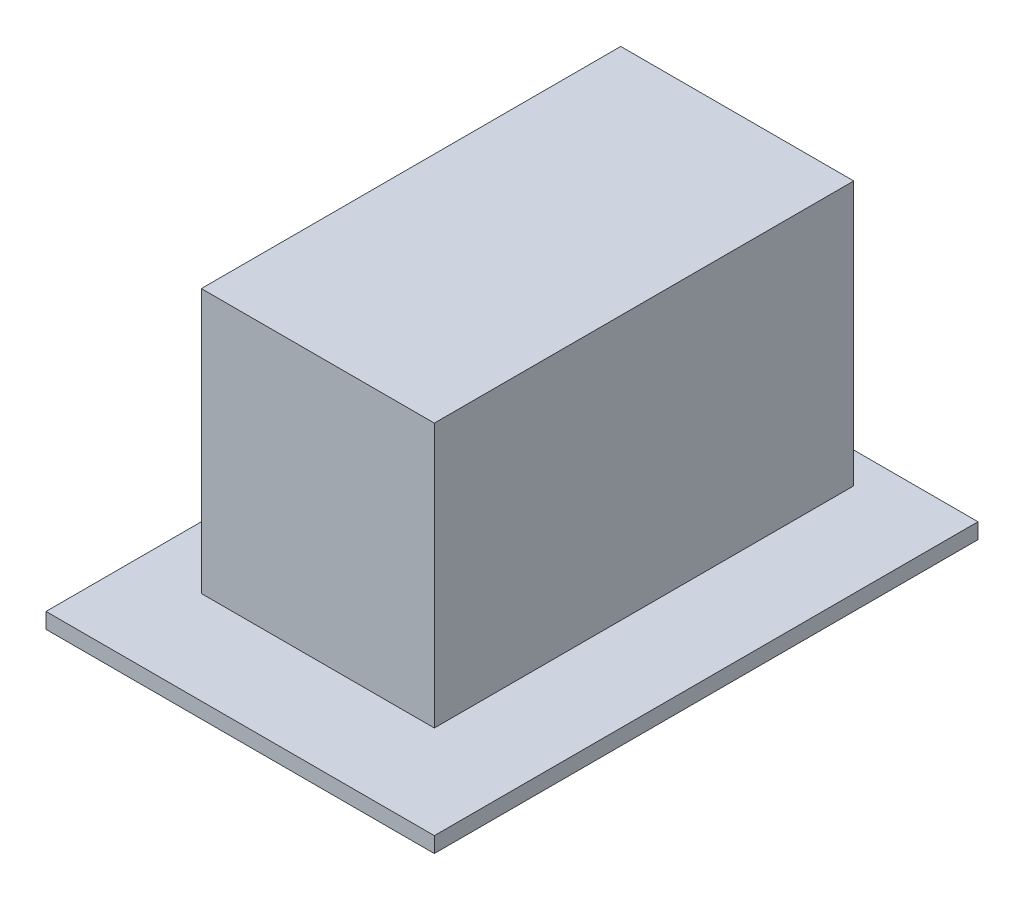
SolidWorks part; units mm, degrees
ref_plane "Plano frontal" through (0, 0, 0) normal (0, 0, 1) x (1, 0, 0)
ref_plane "Plano superior" through (0, 0, 0) normal (0, 1, 0) x (1, 0, 0)
ref_plane "Plano direito" through (0, 0, 0) normal (1, 0, 0) x (0, 0, -1)
sketch "Esboço1" plane through (0, 0, 0) normal (0, 1, 0) x (1, 0, 0)
  line L1 (-12.5, 17.5) -> (12.5, 17.5)
  line L2 (-12.5, 17.5) -> (-12.5, -17.5)
  line L3 (-12.5, -17.5) -> (12.5, -17.5)
  line L4 (12.5, 17.5) -> (12.5, -17.5)
  line L5 (-12.5, 17.5) -> (12.5, -17.5) construction
  line L6 (-12.5, -17.5) -> (12.5, 17.5) construction
  point P0 (0, 0)
  dimension "D1" = 35
  dimension "D2" = 25
extrude "Ressalto-extrusão1" add sketch "Esboço1" along normal blind 1
sketch "Esboço2" plane through (0, 1, 0) normal (0, 1, 0) x (1, 0, 0)
  line L0 (-12.5, -17.5) -> (12.5, -17.5) construction
  line L1 (-8.5, 15.5) -> (6.5, 15.5)
  line L2 (-8.5, 15.5) -> (-8.5, -11.5)
  line L3 (-8.5, -11.5) -> (6.5, -11.5)
  line L4 (6.5, 15.5) -> (6.5, -11.5)
  line L5 (12.5, -17.5) -> (12.5, 17.5) construction
  dimension "D1" = 27
  dimension "D2" = 6
  dimension "D3" = 15
  dimension "D4" = 6
extrude "Ressalto-extrusão2" add sketch "Esboço2" along normal blind 17
